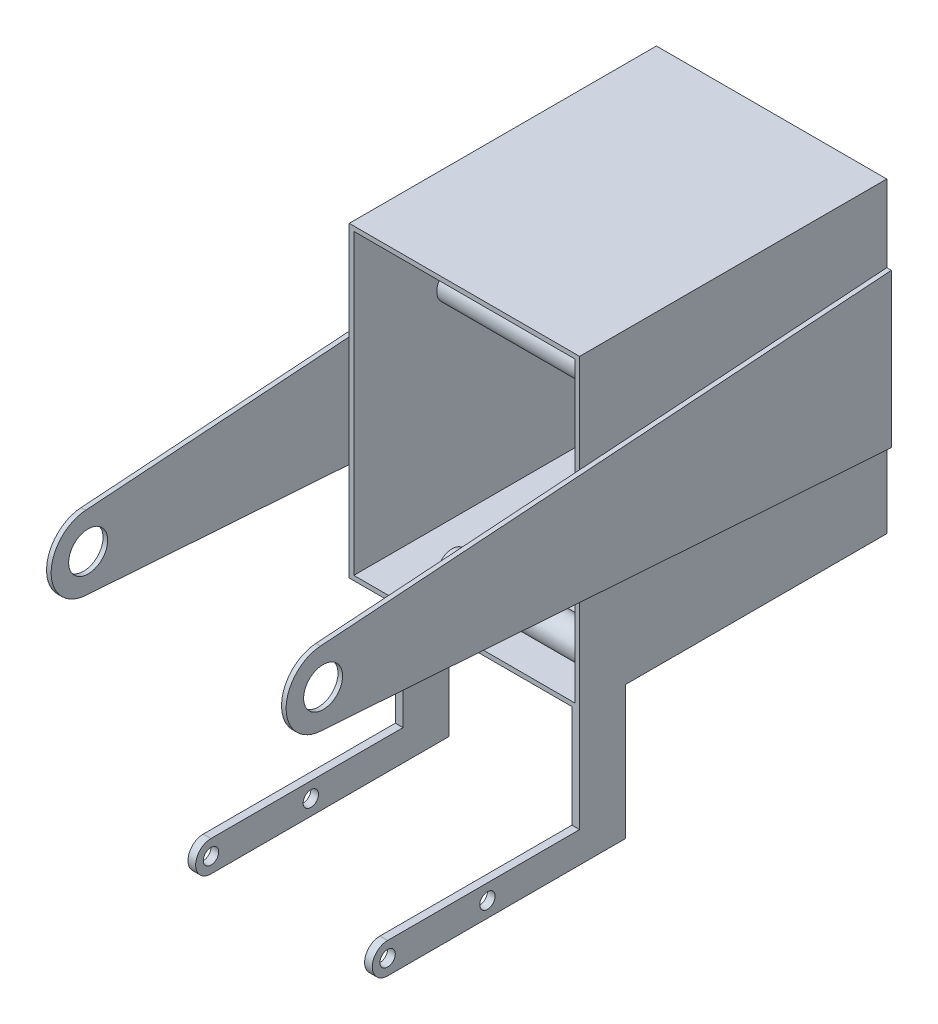
SolidWorks part; units mm, degrees
ref_plane "Alzado" through (0, 0, 0) normal (0, 0, 1) x (1, 0, 0)
ref_plane "Planta" through (0, 0, 0) normal (0, 1, 0) x (1, 0, 0)
ref_plane "Vista lateral" through (0, 0, 0) normal (1, 0, 0) x (0, 0, -1)
sketch "Croquis1" plane through (0, 0, 0) normal (0, 0, 1) x (1, 0, 0)
  line L0 (0, 0) -> (0, 200)
  line L1 (0, 0) -> (150, 0)
  line L2 (0, 200) -> (150, 200)
  line L3 (150, 0) -> (150, 200)
  dimension "D1" = 150
  dimension "D2" = 200
extrude "Saliente-Extruir1" add sketch "Croquis1" along normal blind 200
shell "Vaciado1" thickness 3
sketch "Croquis2" plane through (147, 0, 0) normal (-1, 0, 0) x (0, 0, 1)
  line L0 (0, 200) -> (0, 0) construction
  line L1 (200, 200) -> (200, 0) construction
  line L2 (0, 100) -> (200, 100) construction
  line L3 (200, 200) -> (0, 200) construction
  circle A0 centre (33, 100) radius 10
  circle A1 centre (180, 180) radius 10
  circle A3 centre (180, 20) radius 10
  point P9 (0, 100)
  dimension "D1" = 20
  dimension "D2" = 33
  dimension "D3" = 20
  dimension "D4" = 20
extrude "Saliente-Extruir2" add sketch "Croquis2" along normal blind 100
sketch "Croquis3" plane through (150, 0, 0) normal (1, 0, 0) x (0, 0, -1)
  line L0 (-371.6789, 124.0097) -> (0, 150)
  line L1 (0, 0) -> (0, 200) construction
  line L2 (0, 150) -> (0, 50)
  line L5 (0, 100) -> (-81.8712, 100) construction
  line L6 (-200, 0) -> (-200, 200) construction
  line L7 (-371.6789, 75.9903) -> (0, 50)
  arc A1 (-371.6789, 124.0097) -> (-371.6789, 75.9903) centre (-370, 100) ccw
  circle A2 centre (-370, 100) radius 12.7
  point P11 (-200, 100)
  dimension "D4" = 25.4
  dimension "D1" = 170
  dimension "D2" = 50
  dimension "D3" = 86
extrude "Saliente-Extruir3" add sketch "Croquis3" along normal blind 3
ref_plane "Plano1" through (75, 0, 0) normal (1, 0, 0) x (0, 0, -1)
mirror "Simetría1" about plane through (75, 0, 0) normal (1, 0, 0) of "Saliente-Extruir3"
ref_plane "Plano2" through (30, 0, 0) normal (1, 0, 0) x (0, 0, -1)
sketch "Croquis6" plane through (30, 0, 0) normal (1, 0, 0) x (0, 0, -1)
  line L0 (-200, 0) -> (-200, -66.8651)
  line L3 (-170, -86.8651) -> (-170, 0)
  line L4 (-200, 0) -> (0, 0) construction
  line L5 (-200, 0) -> (-170, 0)
  line L6 (-200, -66.8651) -> (-325, -66.8651)
  line L7 (-325, -86.8651) -> (-170, -86.8651)
  circle A1 centre (-370, 100) radius 150 construction
  circle A2 centre (-260, -76.8651) radius 32.5 construction
  circle A3 centre (-325, -76.8651) radius 32.5 construction
  arc A4 (-325, -66.8651) -> (-325, -86.8651) centre (-325, -76.8651) ccw
  circle A5 centre (-325, -76.8651) radius 5
  circle A6 centre (-260, -76.8651) radius 5
  dimension "D5" = 300
  dimension "D6" = 65
  dimension "D2" = 10
  dimension "D1" = 20
  dimension "D3" = 60
  dimension "D4" = 30
extrude "Saliente-Extruir4" add sketch "Croquis6" along normal blind 5
sketch "Croquis8" plane through (150, 0, 0) normal (1, 0, 0) x (0, 0, -1)
  line L5 (-200, -66.8651) -> (-325, -66.8651)
  line L6 (-200, 0) -> (-200, -66.8651)
  line L7 (-170, 0) -> (-200, 0)
  line L8 (-170, -86.8651) -> (-170, 0)
  line L9 (-325, -86.8651) -> (-170, -86.8651)
  line L10 (-200, -66.8651) -> (-325, -66.8651)
  line L11 (-200, 0) -> (-200, -66.8651)
  line L12 (-170, 0) -> (-200, 0)
  line L13 (-170, -86.8651) -> (-170, 0)
  line L14 (-325, -86.8651) -> (-170, -86.8651)
  circle A1 centre (-260, -76.8651) radius 5
  circle A2 centre (-260, -76.8651) radius 5
  circle A3 centre (-325, -76.8651) radius 5
  circle A4 centre (-325, -76.8651) radius 5
  arc A5 (-325, -66.8651) -> (-325, -86.8651) centre (-325, -76.8651) ccw
  arc A6 (-325, -66.8651) -> (-325, -86.8651) centre (-325, -76.8651) ccw
  dimension "D1" = 0
  dimension "D2" = 0
  dimension "D3" = 0
extrude "Saliente-Extruir5" add sketch "Croquis8" against normal blind 5
